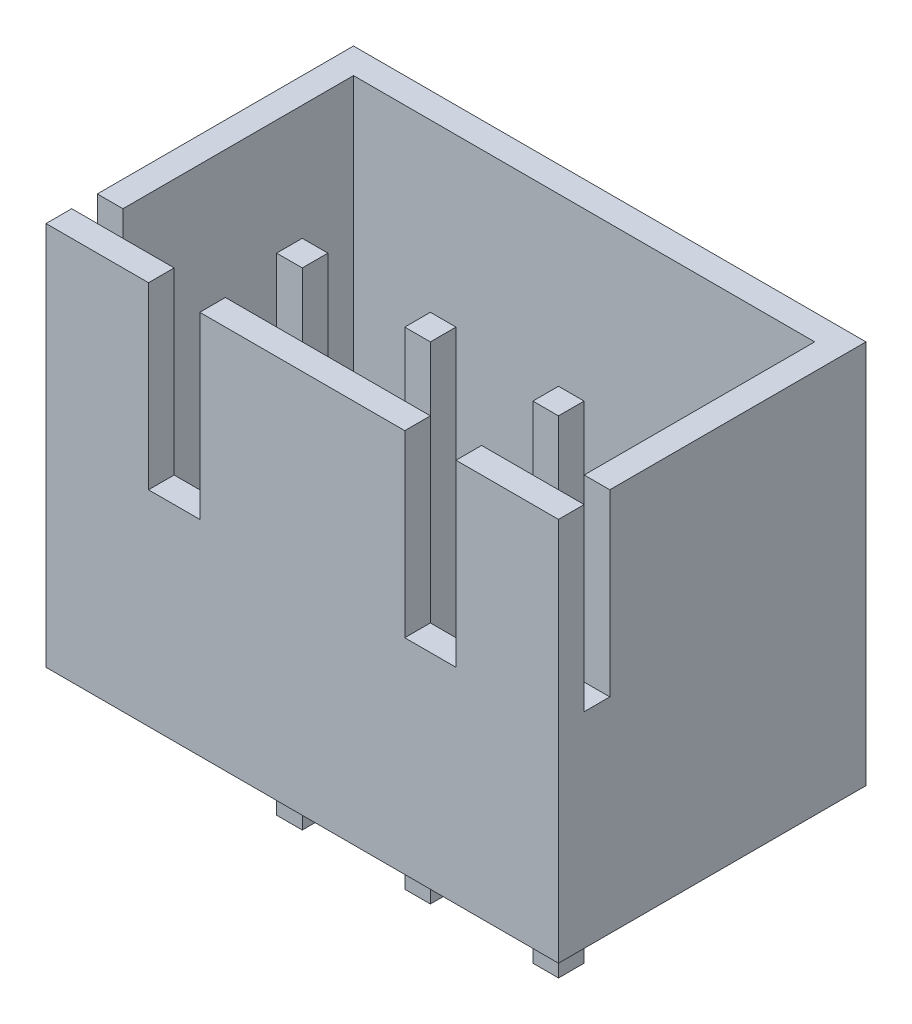
SolidWorks part; units mm, degrees
ref_plane "前视基准面" through (0, 0, 0) normal (0, 0, 1) x (1, 0, 0)
ref_plane "上视基准面" through (0, 0, 0) normal (0, 1, 0) x (1, 0, 0)
ref_plane "右视基准面" through (0, 0, 0) normal (1, 0, 0) x (0, 0, -1)
sketch "草图1" plane through (0, 0, 0) normal (0, 1, 0) x (1, 0, 0)
  line L1 (5, -3) -> (-5, -3)
  line L2 (5, -3) -> (5, 3)
  line L3 (5, 3) -> (-5, 3)
  line L4 (-5, -3) -> (-5, 3)
  line L5 (5, -3) -> (-5, 3) construction
  line L6 (5, 3) -> (-5, -3) construction
  point P0 (0, 0)
  dimension "D1" = 10
  dimension "D2" = 6
extrude "凸台-拉伸1" add sketch "草图1" along normal blind 7.5
shell "抽壳1" thickness 0.5
sketch "草图2" plane through (0, 7.5, 0) normal (0, 1, 0) x (1, 0, 0)
  line L0 (0, 0) -> (0, -5.5842) construction
  line L1 (-6.5881, -1.999) -> (7.0336, -1.999)
  line L2 (-6.5881, -1.999) -> (-6.5881, -2.499)
  line L3 (-6.5881, -2.499) -> (7.0336, -2.499)
  line L4 (7.0336, -1.999) -> (7.0336, -2.499)
  line L5 (-3, -2.5) -> (-2, -2.5)
  line L6 (-3, -2.5) -> (-3, -3.61)
  line L7 (-3, -3.61) -> (-2, -3.61)
  line L8 (-2, -2.5) -> (-2, -3.61)
  line L9 (2, -2.5) -> (3, -2.5)
  line L10 (2, -2.5) -> (2, -3.61)
  line L11 (2, -3.61) -> (3, -3.61)
  line L12 (3, -2.5) -> (3, -3.61)
  line L13 (-5, -3) -> (5, -3) construction
  line L14 (-4.5, -2.5) -> (4.5, -2.5) construction
  dimension "D1" = 4
  dimension "D2" = 1
  dimension "D3" = 0.5
  dimension "D4" = 0.501
extrude "切除-拉伸1" cut sketch "草图2" against normal blind 3.5
sketch "草图3" plane through (0, 0.5, 0) normal (0, 1, 0) x (1, 0, 0)
  line L0 (0, -0.5) -> (0, -1.9417) construction
  line L1 (-0.25, -0.75) -> (0.25, -0.75)
  line L2 (-0.25, -0.75) -> (-0.25, -0.25)
  line L3 (-0.25, -0.25) -> (0.25, -0.25)
  line L4 (0.25, -0.75) -> (0.25, -0.25)
  line L5 (-0.25, -0.75) -> (0.25, -0.25) construction
  line L6 (-0.25, -0.25) -> (0.25, -0.75) construction
  line L7 (-2.25, -0.75) -> (-2.75, -0.75)
  line L8 (-2.25, -0.75) -> (-2.25, -0.25)
  line L9 (-2.25, -0.25) -> (-2.75, -0.25)
  line L10 (-2.75, -0.75) -> (-2.75, -0.25)
  line L11 (-2.25, -0.75) -> (-2.75, -0.25) construction
  line L12 (-2.25, -0.25) -> (-2.75, -0.75) construction
  line L13 (2.75, -0.75) -> (2.25, -0.75)
  line L14 (2.75, -0.75) -> (2.75, -0.25)
  line L15 (2.75, -0.25) -> (2.25, -0.25)
  line L16 (2.25, -0.75) -> (2.25, -0.25)
  line L17 (2.75, -0.75) -> (2.25, -0.25) construction
  line L18 (2.75, -0.25) -> (2.25, -0.75) construction
  line L19 (-4.5, -2.5) -> (4.5, -2.5) construction
  point P0 (0, -0.5)
  point P5 (-2.5, -0.5)
  point P10 (2.5, -0.5)
  dimension "D1" = 0.5
  dimension "D2" = 2.5
  dimension "D3" = 2
extrude "凸台-拉伸2" add sketch "草图3" along normal offset from surface 0.5 and the other way blind 3 up to face at (0, 7.5, -0.3755)
